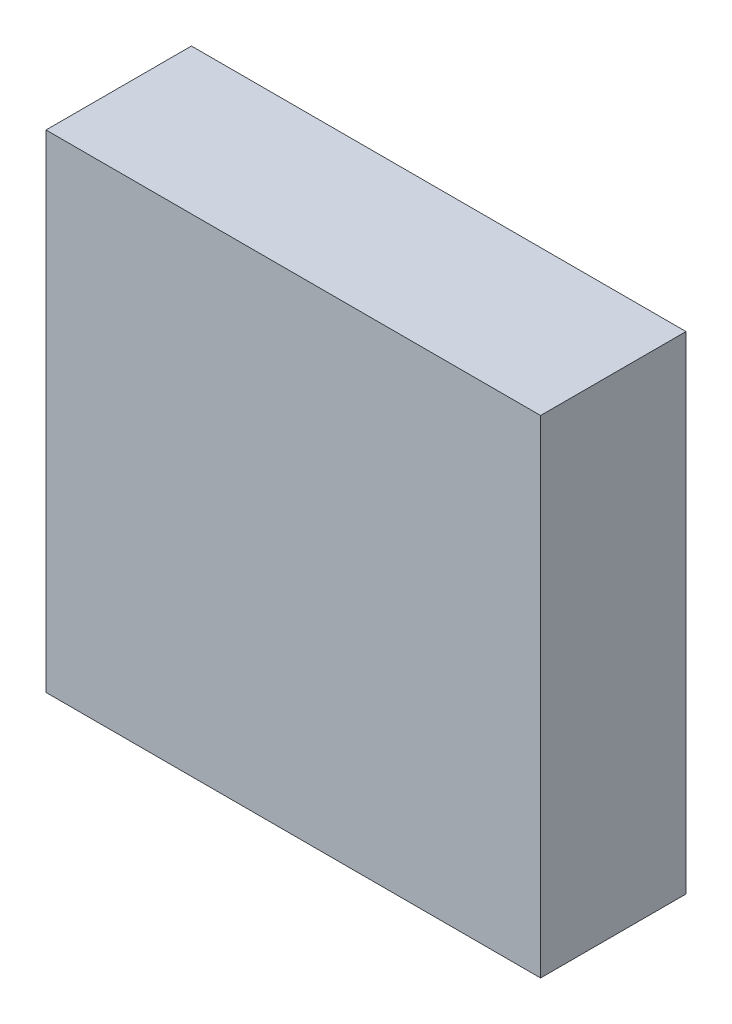
SolidWorks part; units mm, degrees
ref_plane "Front Plane" through (0, 0, 0) normal (0, 0, 1) x (1, 0, 0)
ref_plane "Top Plane" through (0, 0, 0) normal (0, 1, 0) x (1, 0, 0)
ref_plane "Right Plane" through (0, 0, 0) normal (1, 0, 0) x (0, 0, -1)
sketch "Sketch1" plane through (0, 0, 0) normal (0, 0, 1) x (1, 0, 0)
  line L0 (-1.75, 1.6) -> (1.651, 1.6)
  line L1 (1.651, 1.6) -> (1.651, -1.75)
  line L2 (1.651, -1.75) -> (-1.75, -1.75)
  line L3 (-1.75, -1.75) -> (-1.75, 1.6)
extrude "Component_Outline" add sketch "Sketch1" along normal blind 1 separate body
sketch3d "3DSketch1"
  line L0 (0, 0, 0) -> (1, 0, 0)
  line L1 (0, 0, 0) -> (0, 1, 0)
  line L2 (0, 0, 0) -> (0, 0, 1)
  point P0 (0, 0, 0)
